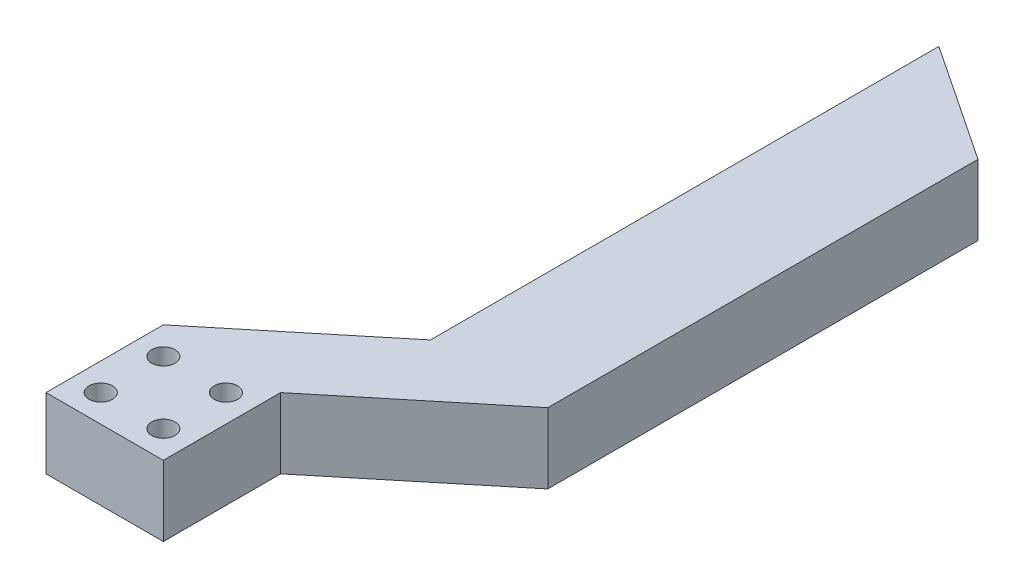
SolidWorks part; units mm, degrees
ref_plane "Alzado" through (0, 0, 0) normal (0, 0, 1) x (1, 0, 0)
ref_plane "Planta" through (0, 0, 0) normal (0, 1, 0) x (1, 0, 0)
ref_plane "Vista lateral" through (0, 0, 0) normal (1, 0, 0) x (0, 0, -1)
sketch "Croquis1" plane through (0, 0, 0) normal (0, 1, 0) x (1, 0, 0)
  line L0 (0, 0) -> (0, 17.1196) construction
  line L1 (7.75, 7.5) -> (26.5, 22.9043)
  line L2 (7.75, -7.5) -> (22.75, -7.5)
  line L3 (7.75, -7.5) -> (7.75, 7.5)
  line L5 (22.75, -7.5) -> (22.75, 7.5)
  line L6 (7.75, -7.5) -> (22.75, 7.5) construction
  line L7 (7.75, 7.5) -> (22.75, -7.5) construction
  line L9 (26.5, 77.9043) -> (26.5, 22.9043)
  line L11 (41.5, 77.9043) -> (41.5, 22.9043)
  line L12 (26.5, 77.9043) -> (41.5, 22.9043) construction
  line L13 (26.5, 22.9043) -> (41.5, 77.9043) construction
  line L16 (22.75, 7.5) -> (41.5, 22.9043)
  line L17 (26.5, 77.9043) -> (26.5, 87.9043)
  line L18 (26.5, 87.9043) -> (41.5, 77.9043)
  circle A0 centre (19.25, 4) radius 1.5
  circle A1 centre (19.25, -4) radius 1.5
  circle A2 centre (11.25, -4) radius 1.5
  circle A3 centre (11.25, 4) radius 1.5
  point P3 (15.25, 0)
  point P10 (34, 50.4043)
  point P25 (15.25, 0)
  dimension "D11" = 3
  dimension "D1" = 15
  dimension "D2" = 15
  dimension "D3" = 15.25
  dimension "D4" = 26.5
  dimension "D5" = 55
  dimension "D6" = 10
  dimension "D7" = 24.2663
  dimension "D8" = 21.2132
  dimension "D9" = 15
  dimension "D10" = 18.0278
  dimension "D12" = 4
  dimension "D14" = 4
  dimension "D13" = 4
extrude "Saliente-Extruir1" add sketch "Croquis1" along normal blind 9
